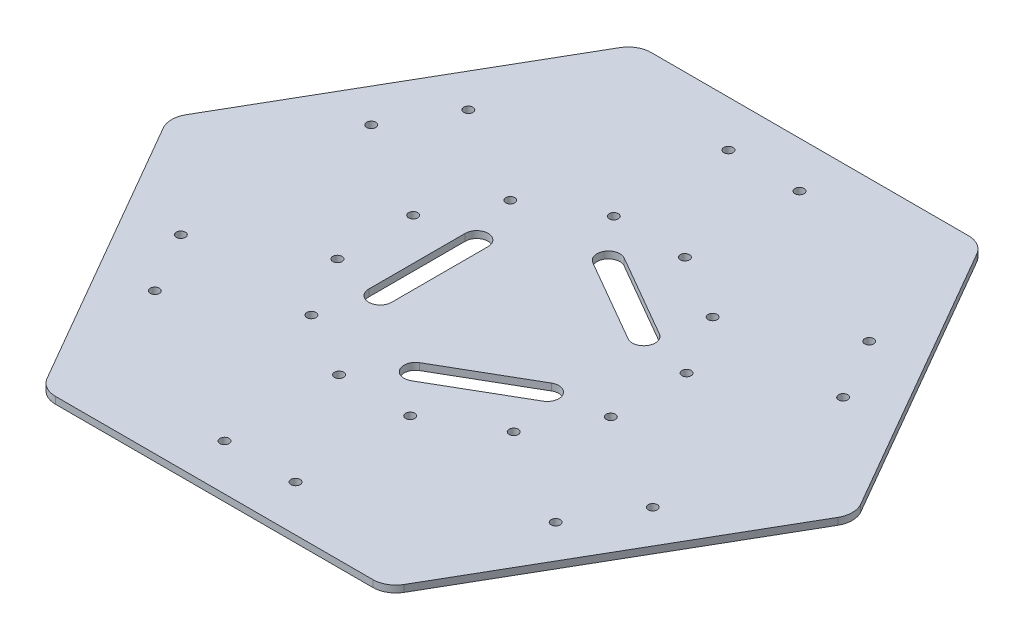
SolidWorks part; units mm, degrees
ref_plane "Plan de face" through (0, 0, 0) normal (0, 0, 1) x (1, 0, 0)
ref_plane "Plan de dessus" through (0, 0, 0) normal (0, 1, 0) x (1, 0, 0)
ref_plane "Plan de droite" through (0, 0, 0) normal (1, 0, 0) x (0, 0, -1)
sketch "Esquisse1" plane through (0, 0, 0) normal (0, 1, 0) x (1, 0, 0)
  line L0 (-150, 0) -> (-75, 129.9038) construction
  line L7 (-150, 0) -> (-75, -129.9038)
  line L8 (-75, -129.9038) -> (75, -129.9038)
  line L9 (75, -129.9038) -> (150, 0)
  line L10 (150, 0) -> (75, 129.9038)
  line L11 (75, 129.9038) -> (-75, 129.9038)
  line L12 (-75, 129.9038) -> (-150, 0)
  line L29 (-150, 0) -> (150, 0) construction
  line L30 (0, 129.9038) -> (0, -129.9038) construction
  line L31 (-75, -129.9038) -> (-75, 129.9038) construction
  line L32 (75, 129.9038) -> (75, -129.9038) construction
  line L33 (-150, 0) -> (78.9579, -132.1889) construction
  line L34 (150, 0) -> (-75, 129.9038) construction
  line L35 (-75, -129.9038) -> (150, 0) construction
  line L36 (-150, 0) -> (75, 129.9038) construction
  line L37 (-112.5, -64.9519) -> (112.5, 64.9519) construction
  line L38 (-112.5, 64.9519) -> (112.5, -64.9519) construction
  circle A0 centre (0, 0) radius 129.9038 construction
  circle A1 centre (15.5, -109.9038) radius 2
  circle A2 centre (-15.5, -109.9038) radius 2
  circle A3 centre (15.5, -59.9038) radius 2
  circle A4 centre (-15.5, -59.9038) radius 2
  circle A5 centre (-87.4295, -68.3753) radius 2
  circle A6 centre (-102.9295, -41.5285) radius 2
  circle A7 centre (-59.6282, -16.5285) radius 2
  circle A8 centre (-44.1282, -43.3753) radius 2
  circle A9 centre (-102.9295, 41.5285) radius 2
  circle A10 centre (-87.4295, 68.3753) radius 2
  circle A11 centre (-44.1282, 43.3753) radius 2
  circle A12 centre (-59.6282, 16.5285) radius 2
  circle A13 centre (-15.5, 109.9038) radius 2
  circle A14 centre (15.5, 109.9038) radius 2
  circle A15 centre (15.5, 59.9038) radius 2
  circle A16 centre (-15.5, 59.9038) radius 2
  circle A17 centre (87.4295, 68.3753) radius 2
  circle A18 centre (102.9295, 41.5285) radius 2
  circle A19 centre (59.6282, 16.5285) radius 2
  circle A20 centre (44.1282, 43.3753) radius 2
  circle A21 centre (102.9295, -41.5285) radius 2
  circle A22 centre (87.4295, -68.3753) radius 2
  circle A23 centre (44.1282, -43.3753) radius 2
  circle A24 centre (59.6282, -16.5285) radius 2
  point P1 (-112.5, 64.9519)
  point P11 (0, 129.9038)
  point P12 (-150, 0)
  point P69 (0, 0)
  dimension "D6" = 50
  dimension "D7" = 4
  dimension "D1" = 150
  dimension "D2" = 259.8076
  dimension "D3" = 129.9038
  dimension "D4" = 15.5
  dimension "D5" = 20
  dimension "D8" = 15.5
  dimension "D9" = 6
extrude "Boss.-Extru.1" add sketch "Esquisse1" along normal blind 3
fillet "Congé2" radius 10 1 edges at (-75, 1.5, -129.9038)
fillet "Congé3" radius 10 5 edges at (75, 1.5, -129.9038) (150, 1.5, 0) (75, 1.5, 129.9038) (-75, 1.5, 129.9038) (-150, 1.5, 0)
sketch "Esquisse3" plane through (0, 3, 0) normal (0, 1, 0) x (1, 0, 0)
  line L15 (0, 129.9038) -> (0, -129.9038) construction
  line L16 (-44.8782, 42.0763) -> (44.8782, 42.0763) construction
  line L17 (112.5, 64.9519) -> (-112.5, -64.9519) construction
  line L18 (14, 59.9038) -> (58.8782, -17.8275) construction
  line L19 (0, 42.0763) -> (36.4391, 21.0381) construction
  line L20 (2.5, 46.4064) -> (38.9391, 25.3683)
  line L21 (-2.5, 37.7461) -> (33.9391, 16.708)
  line L22 (36.4391, -21.0381) -> (0, -42.0763) construction
  line L23 (38.9391, -25.3683) -> (2.5, -46.4064)
  line L24 (33.9391, -16.708) -> (-2.5, -37.7461)
  line L25 (-36.4391, -21.0381) -> (-36.4391, 21.0381) construction
  line L26 (-41.4391, -21.0381) -> (-41.4391, 21.0381)
  line L27 (-31.4391, -21.0381) -> (-31.4391, 21.0381)
  arc A0 (2.5, 46.4064) -> (-2.5, 37.7461) centre (0, 42.0763) ccw
  arc A1 (33.9391, 16.708) -> (38.9391, 25.3683) centre (36.4391, 21.0381) ccw
  arc A2 (38.9391, -25.3683) -> (33.9391, -16.708) centre (36.4391, -21.0381) ccw
  arc A3 (-2.5, -37.7461) -> (2.5, -46.4064) centre (0, -42.0763) ccw
  arc A4 (-41.4391, -21.0381) -> (-31.4391, -21.0381) centre (-36.4391, -21.0381) ccw
  arc A5 (-31.4391, 21.0381) -> (-41.4391, 21.0381) centre (-36.4391, 21.0381) ccw
  point P24 (0, 0)
  point P33 (18.2196, 31.5572)
  point P40 (18.2196, -31.5572)
  point P47 (-36.4391, 0)
  point P52 (0, 0)
extrude "Enlèv. mat.-Extru.1" cut sketch "Esquisse3" against normal through all
